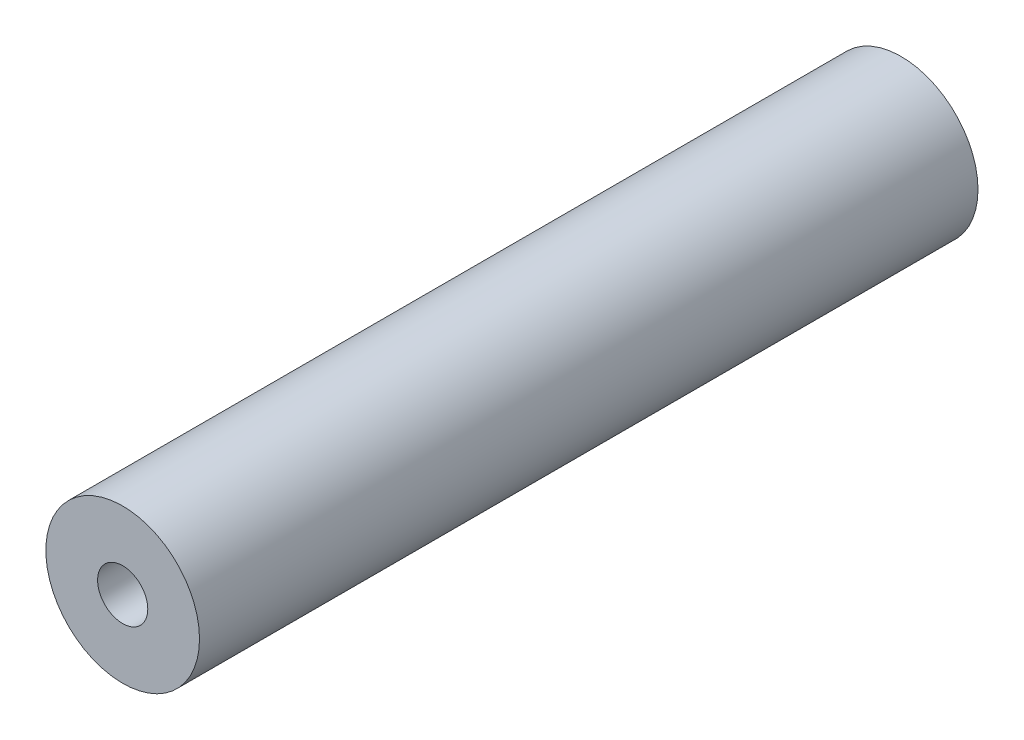
SolidWorks part; units mm, degrees
material "ABS"
ref_plane "前基準面" through (0, 0, 0) normal (0, 0, 1) x (1, 0, 0)
ref_plane "上基準面" through (0, 0, 0) normal (0, 1, 0) x (1, 0, 0)
ref_plane "右基準面" through (0, 0, 0) normal (1, 0, 0) x (0, 0, -1)
sketch "草圖1" plane through (0, 0, 0) normal (0, 0, 1) x (1, 0, 0)
  circle A1 centre (0, 0) radius 15
  circle A2 centre (0, 0) radius 4.9
  dimension "D1" = 9.8
  dimension "D2" = 30
extrude "填料-伸長1" add sketch "草圖1" along normal blind 152
